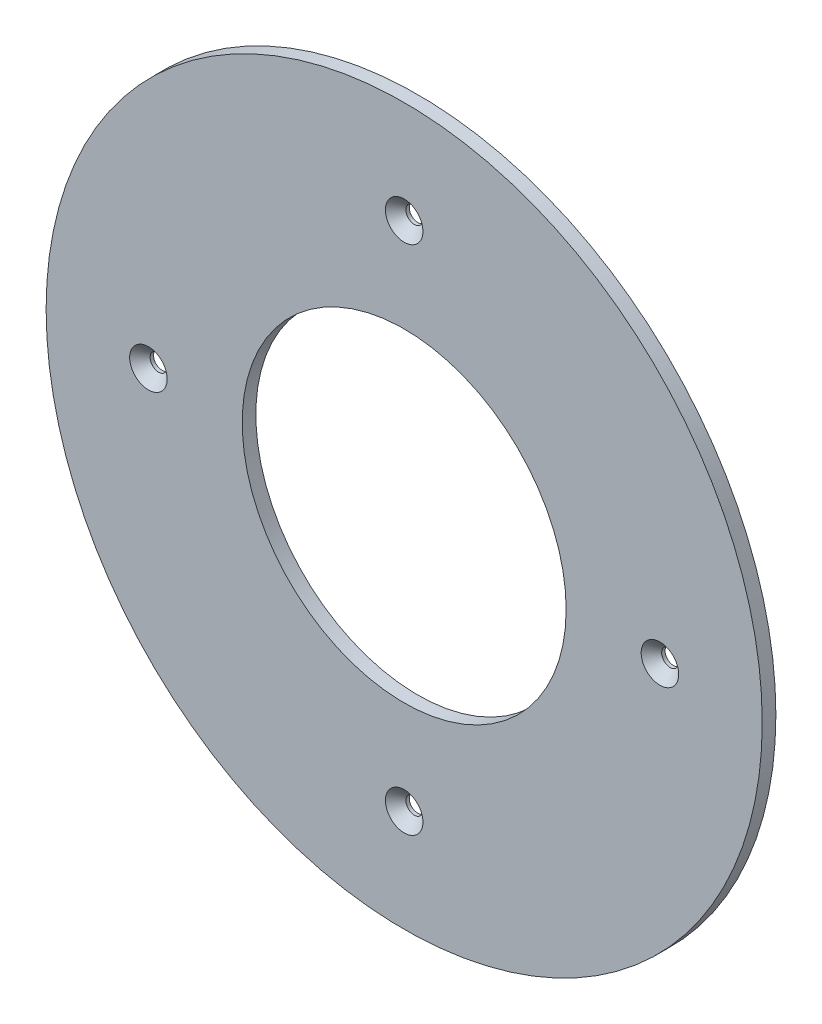
SolidWorks part; units mm, degrees
ref_plane "Front" through (0, 0, 0) normal (0, 0, 1) x (1, 0, 0)
ref_plane "Top" through (0, 0, 0) normal (0, 1, 0) x (1, 0, 0)
ref_plane "Right" through (0, 0, 0) normal (1, 0, 0) x (0, 0, -1)
sketch "Sketch1" plane through (0, 0, 0) normal (0, 0, 1) x (1, 0, 0)
  line L0 (-75, 0) -> (0, 0) construction
  line L1 (0, 0) -> (75, 0) construction
  line L2 (0, 75) -> (0, 0) construction
  line L3 (0, -75) -> (0, 0) construction
  circle A0 centre (0, 0) radius 105
  circle A1 centre (0, 0) radius 47.5
  circle A2 centre (0, 75) radius 2.5
  circle A3 centre (75, 0) radius 2.5
  circle A4 centre (0, -75) radius 2.5
  circle A5 centre (-75, 0) radius 2.5
  dimension "D1" = 210
  dimension "D2" = 95
  dimension "D3" = 5
  dimension "D4" = 75
extrude "Boss-Extrude1" add sketch "Sketch1" along normal blind 4
chamfer "Chamfer1" distance 3 angle 45 4 edges at (-72.5, 0, 4) (2.5, -75, 4) (77.5, 0, 4) (2.5, 75, 4)
